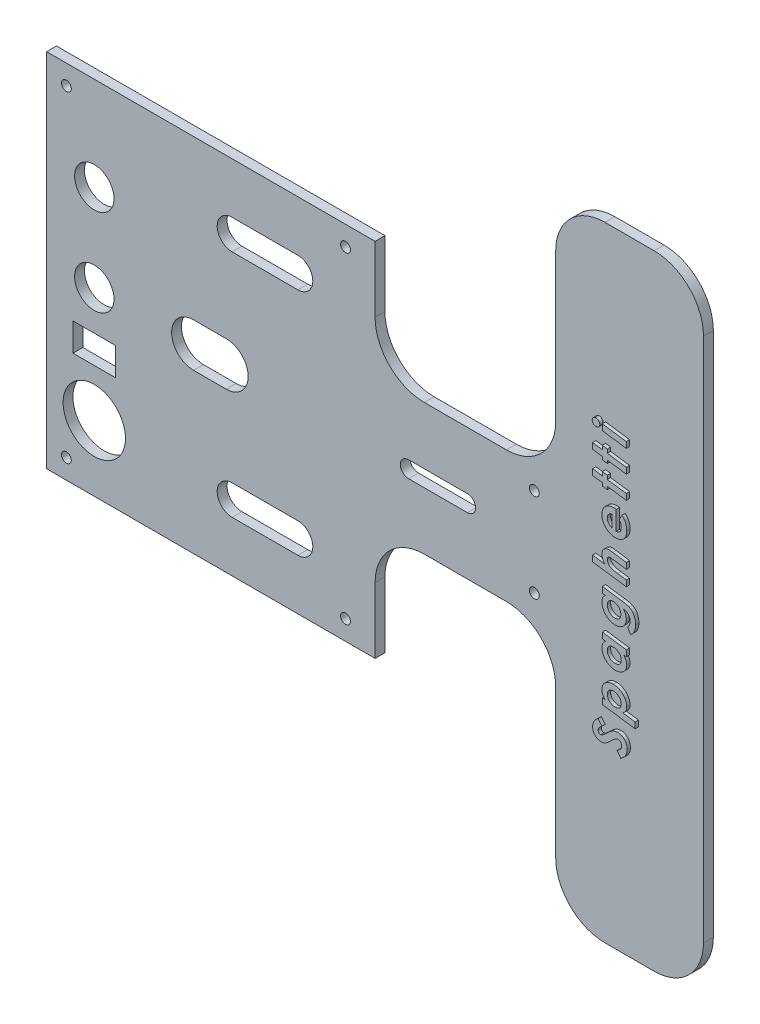
SolidWorks part; units mm, degrees
ref_plane "Front Plane" through (0, 0, 0) normal (0, 0, 1) x (1, 0, 0)
ref_plane "Top Plane" through (0, 0, 0) normal (0, 1, 0) x (1, 0, 0)
ref_plane "Right Plane" through (0, 0, 0) normal (1, 0, 0) x (0, 0, -1)
sketch "Sketch1" plane through (0, 0, 0) normal (0, 0, 1) x (1, 0, 0)
  line L1 (77.5, 55) -> (-77.5, 55)
  line L2 (77.5, 55) -> (77.5, -55)
  line L3 (77.5, -55) -> (-77.5, -55)
  line L4 (-77.5, 55) -> (-77.5, -55)
  line L5 (77.5, 55) -> (-77.5, -55) construction
  line L6 (77.5, -55) -> (-77.5, 55) construction
  point P0 (0, 0)
  dimension "D1" = 155
  dimension "D2" = 110
extrude "Boss-Extrude1" add sketch "Sketch1" along normal blind 3
sketch "Sketch2" plane through (0, 0, 3) normal (0, 0, 1) x (1, 0, 0)
  line L0 (-77.5, 0) -> (77.5, 0) construction
  line L1 (-77.5, 55) -> (-77.5, -55) construction
  line L2 (77.5, -55) -> (77.5, 55) construction
  line L3 (77.5, -20) -> (77.5, -55)
  line L4 (22.5, 20) -> (77.5, 20)
  line L5 (22.5, 20) -> (22.5, 55)
  line L6 (77.5, 55) -> (-77.5, 55) construction
  line L7 (22.5, -20) -> (22.5, -55)
  line L8 (22.5, -20) -> (77.5, -20)
  line L9 (77.5, -55) -> (22.5, -55)
  line L10 (22.5, 55) -> (77.5, 55)
  line L11 (77.5, 55) -> (77.5, 20)
  line L12 (-77.5, -55) -> (77.5, -55) construction
  line L17 (-56.5001, -12) -> (-69.5001, -12)
  line L18 (-56.5001, -12) -> (-56.5001, -20.5)
  line L19 (-56.5001, -20.5) -> (-69.5001, -20.5)
  line L20 (-69.5001, -12) -> (-69.5001, -20.5)
  line L21 (-56.5001, -12) -> (-69.5001, -20.5) construction
  line L22 (-56.5001, -20.5) -> (-69.5001, -12) construction
  line L23 (-63, 0) -> (-63, -35) construction
  line L24 (-21.0194, 35) -> (-1.0194, 35) construction
  line L25 (-21.0194, 39.5566) -> (-1.0194, 39.5566)
  line L26 (-21.0194, 30.4434) -> (-1.0194, 30.4434)
  line L27 (-21.0194, -35) -> (-1.0194, -35) construction
  line L28 (-21.0194, -39.5566) -> (-1.0194, -39.5566)
  line L29 (-21.0194, -30.4434) -> (-1.0194, -30.4434)
  line L30 (-27.5, 55) -> (-27.5, -55) construction
  line L31 (32.6717, 0) -> (50.6001, 0) construction
  line L32 (32.6717, 2.5) -> (50.6001, 2.5)
  line L33 (32.6717, -2.5) -> (50.6001, -2.5)
  circle A1 centre (-63, -35) radius 9.5
  circle A2 centre (-63, 0) radius 6
  circle A4 centre (-63, 26.5) radius 6
  arc A5 (-21.0194, 39.5566) -> (-21.0194, 30.4434) centre (-21.0194, 35) ccw
  arc A6 (-1.0194, 30.4434) -> (-1.0194, 39.5566) centre (-1.0194, 35) ccw
  arc A7 (-21.0194, -39.5566) -> (-21.0194, -30.4434) centre (-21.0194, -35) cw
  arc A8 (-1.0194, -30.4434) -> (-1.0194, -39.5566) centre (-1.0194, -35) cw
  circle A9 centre (-71.5, 49) radius 1.5
  circle A10 centre (-71.5, -49) radius 1.5
  circle A14 centre (71, 13.5) radius 1.5
  arc A15 (32.6717, 2.5) -> (32.6717, -2.5) centre (32.6717, 0) ccw
  arc A16 (50.6001, -2.5) -> (50.6001, 2.5) centre (50.6001, 0) ccw
  circle A17 centre (71, -13.5) radius 1.5
  circle A18 centre (13.5, 49) radius 1.5
  circle A19 centre (13.5, -49) radius 1.5
  point P8 (22.5, 0)
  point P9 (-49.5, 0)
  point P10 (22.5, 20)
  point P27 (-63.0001, -16.25)
  point P36 (-11.0194, 35)
  point P43 (-11.0194, -35)
  point P50 (-77.5, 55)
  point P51 (-27.5, 55)
  point P63 (-35.6542, 0)
  point P66 (41.6359, 0)
  dimension "D2" = 19
  dimension "D4" = 14.5
  dimension "D6" = 12
  dimension "D7" = 12
  dimension "D11" = 26.5
  dimension "D14" = 20
  dimension "D15" = 3
  dimension "D16" = 6
  dimension "D19" = 3
  dimension "D20" = 6.5
  dimension "D21" = 6.5
  dimension "D23" = 3
  dimension "D24" = 9
  dimension "D1" = 72
  dimension "D3" = 55
  dimension "D5" = 20
  dimension "D8" = 13
  dimension "D9" = 8.5
  dimension "D10" = 14.5
  dimension "D12" = 20
  dimension "D13" = 20
  dimension "D17" = 6
  dimension "D18" = 50
  dimension "D22" = 5
extrude "Cut-Extrude1" cut sketch "Sketch2" against normal blind 148 contours L9 L7 L8 L3 | L11 L4 L5 L10 | A1 | L18 L17 L20 L19 | A2 | A4 | L26 A6 L25 A5 | L28 A8 L29 A7 | A9 | A10 | A18 | A19 | A14 | L33 A16 L32 A15 | A17
sketch3d "3DSketch1"
  point P0 (57.5415, 7.1901, 3)
ref_plane "Plane1" through (0, 0, 3) normal (0, 0, 1) x (1, 0, 0)
sketch "Sketch5" plane through (0, 0, 3) normal (0, 0, 1) x (1, 0, 0)
  line L0 (77.5, 20) -> (77.5, 95)
  line L1 (77.5, 95) -> (122.5, 95)
  line L2 (122.5, 95) -> (122.5, -95)
  line L3 (0, 0) -> (122.5, 0) construction
  line L4 (77.5, -95) -> (122.5, -95)
  line L5 (77.5, -20) -> (77.5, -95)
  line L6 (77.5, 20) -> (77.5, -20)
  dimension "D1" = 95
  dimension "D2" = 45
extrude "Boss-Extrude3" add sketch "Sketch5" against normal blind 3
fillet "Fillet1" radius 15 8 edges at (77.5, 20, 1.5) (77.5, -20, 1.5) (22.5, -20, 1.5) (77.5, -95, 1.5) (22.5, 20, 1.5) (77.5, 95, 1.5) (122.5, 95, 1.5) (122.5, -95, 1.5)
sketch "Sketch8" plane through (0, 0, 3) normal (0, 0, 1) x (1, 0, 0)
  line L0 (100, 95) -> (100, -95) construction
  line L1 (107.5, 95) -> (92.5, 95) construction
  line L2 (92.5, -95) -> (107.5, -95) construction
  text T0 "Spaghetti" font "Century Gothic" height 10
sketch "Sketch9" plane through (0, 0, 3) normal (0, 0, 1) x (1, 0, 0)
  line L0 (-32.7959, 0) -> (-22.7959, 0) construction
  line L1 (-32.7959, 6.6519) -> (-22.7959, 6.6519)
  line L2 (-32.7959, -6.6519) -> (-22.7959, -6.6519)
  arc A0 (-32.7959, 6.6519) -> (-32.7959, -6.6519) centre (-32.7959, 0) ccw
  arc A1 (-22.7959, -6.6519) -> (-22.7959, 6.6519) centre (-22.7959, 0) ccw
  point P3 (-27.7959, 0)
  dimension "D1" = 10
extrude "Cut-Extrude4" cut sketch "Sketch9" against normal blind 98
extrude "Boss-Extrude5" add sketch "Sketch8" along normal blind 1
